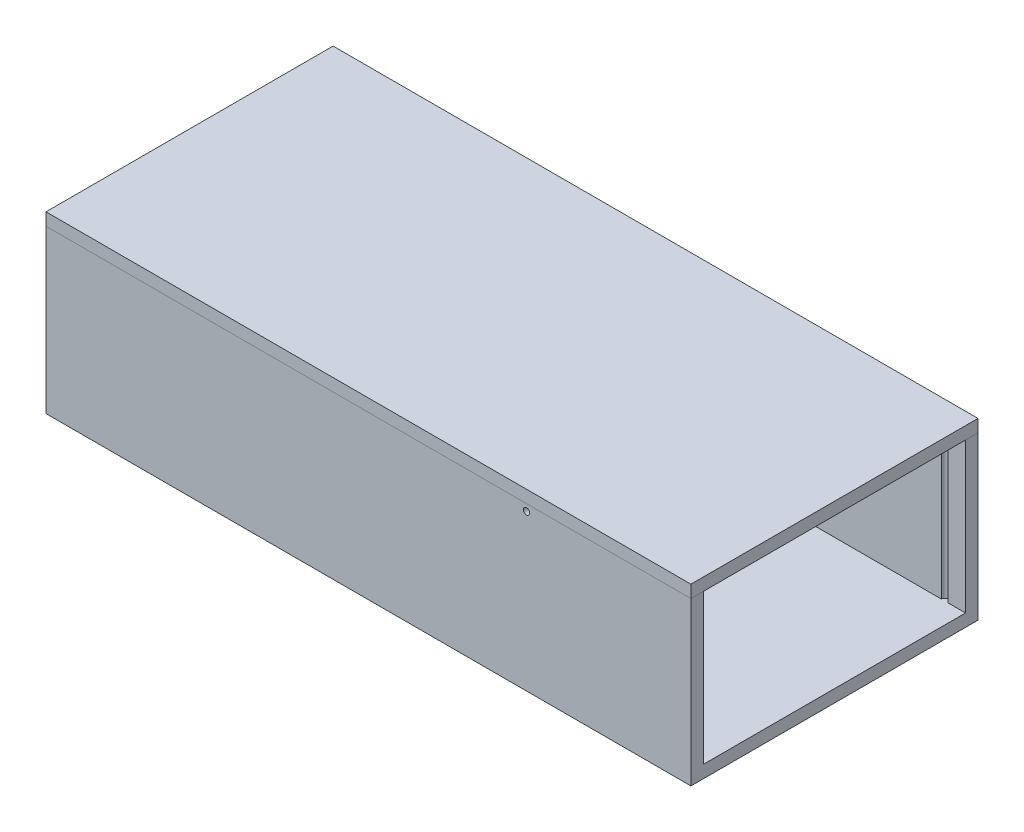
SolidWorks part; units mm, degrees
ref_plane "Plano frontal" through (0, 0, 0) normal (0, 0, 1) x (1, 0, 0)
ref_plane "Plano superior" through (0, 0, 0) normal (0, 1, 0) x (1, 0, 0)
ref_plane "Plano direito" through (0, 0, 0) normal (1, 0, 0) x (0, 0, -1)
sketch "Esboço1" plane through (0, 0, 0) normal (0, 1, 0) x (1, 0, 0)
  line L1 (0, 0) -> (155, 0)
  line L2 (0, 0) -> (0, 69)
  line L3 (0, 69) -> (155, 69)
  line L4 (155, 0) -> (155, 69)
  dimension "D1" = 69
  dimension "D2" = 155
extrude "Ressalto-extrusão1" add sketch "Esboço1" along normal blind 39
sketch "Esboço2" plane through (0, 39, 0) normal (0, 1, 0) x (1, 0, 0)
  line L0 (0, 0) -> (155, 0) construction
  line L1 (2, 3) -> (155, 3)
  line L2 (2, 3) -> (2, 66)
  line L3 (2, 66) -> (155, 66)
  line L4 (155, 3) -> (155, 66)
  line L5 (155, 69) -> (0, 69) construction
  line L6 (0, 69) -> (0, 0) construction
  dimension "D1" = 3
  dimension "D2" = 3
  dimension "D3" = 2
  dimension "D4" = 0
extrude "Corte-extrusão1" cut sketch "Esboço2" against normal offset from surface (36 mm away) 3 up to face at (77.5, 0, -34.5)
sketch "Esboço5" plane through (0, 39, 0) normal (0, 1, 0) x (1, 0, 0)
  line L0 (155, 66) -> (155, 69) construction
  line L1 (2, 3) -> (122.5, 3)
  line L2 (2, 3) -> (2, 5)
  line L3 (2, 5) -> (122.5, 5)
  line L4 (122.5, 3) -> (122.5, 5)
  line L5 (2, 66) -> (122.5, 66)
  line L6 (2, 66) -> (2, 64)
  line L7 (2, 64) -> (122.5, 64)
  line L8 (122.5, 66) -> (122.5, 64)
  point P13 (155, 67.5)
  dimension "D1" = 2
  dimension "D2" = 2
  dimension "D3" = 32.5
  dimension "D4" = 32.5
extrude "Ressalto-extrusão3" add sketch "Esboço5" against normal offset from surface (5.4 mm away) 26.5 from offset 4.1 up to face at (78.5, 3, -34.5) offset against normal yes
sketch "Esboço7" plane through (0, 39, 0) normal (0, 1, 0) x (1, 0, 0)
  line L0 (2, 3) -> (155, 3) construction
  line L1 (155, 66) -> (2, 66) construction
  line L2 (155, 66) -> (155, 69) construction
  circle A0 centre (150, 3) radius 0.8
  circle A1 centre (150, 66) radius 0.8
  dimension "D1" = 5
  dimension "D2" = 5
  dimension "D3" = 1.6
  dimension "D4" = 1.6
extrude "Corte-extrusão4" cut sketch "Esboço7" against normal up to surface (36 mm away) up to face at (78.5, 3, -34.5)
fillet "Filete5" [suppressed] radius 3
sketch "Esboço8" plane through (0, 39, 0) normal (0, 1, 0) x (1, 0, 0)
  line L0 (0, 0) -> (155, 0) construction
  line L1 (155, 0) -> (155, 3) construction
  line L2 (0, 69) -> (0, 0) construction
  line L3 (155, 69) -> (0, 69) construction
  line L4 (155, 66) -> (155, 69) construction
  circle A0 centre (3, 3) radius 0.9
  circle A1 centre (120, 3) radius 0.9
  circle A2 centre (120, 66) radius 0.9
  circle A3 centre (3, 66) radius 0.9
  dimension "D1" = 1.8
  dimension "D2" = 1.8
  dimension "D3" = 1.8
  dimension "D4" = 1.8
  dimension "D5" = 3
  dimension "D6" = 35
  dimension "D7" = 3
  dimension "D8" = 3
  dimension "D9" = 3
  dimension "D10" = 3
  dimension "D11" = 35
  dimension "D12" = 3
extrude "Corte-extrusão3" [suppressed] cut sketch "Esboço8" against normal up to surface (8.5 mm away)
sketch "Esboço10" plane through (0, 39, 0) normal (0, 1, 0) x (1, 0, 0)
  line L0 (2, 3) -> (149.2, 3) construction
  line L1 (149.2, 66) -> (2, 66) construction
  line L2 (2, 66) -> (2, 3) construction
  line L3 (2, 66) -> (2, 3) construction
  circle A0 centre (7, 3) radius 0.75
  circle A1 centre (7, 66) radius 0.75
  dimension "D1" = 1.5
  dimension "D2" = 1.5
  dimension "D3" = 5
  dimension "D4" = 5
extrude "Ressalto-extrusão5" add sketch "Esboço10" against normal up to surface (4.1 mm away) up to face at (62.25, 34.9, -4)
sketch "Esboço9" plane through (0, 39, 0) normal (0, 1, 0) x (1, 0, 0)
  line L0 (2, 66) -> (2, 3) construction
  line L1 (155, 0) -> (0, 0)
  line L2 (155, 0) -> (155, 69)
  line L3 (155, 69) -> (0, 69)
  line L4 (0, 0) -> (0, 69)
  line L5 (149.2, 66) -> (7.75, 66) construction
  dimension "D1" = 69
  dimension "D2" = 155
  dimension "D3" = 2
  dimension "D4" = 3
extrude "Ressalto-extrusão4" add sketch "Esboço9" along normal blind 3
sketch "Esboço11" plane through (0, 0, 0) normal (-1, 0, 0) x (0, 0, 1)
  line L1 (-62.35, 37) -> (-44.25, 37)
  line L2 (-62.35, 37) -> (-62.35, 21.9)
  line L3 (-62.35, 21.9) -> (-44.25, 21.9)
  line L4 (-44.25, 37) -> (-44.25, 21.9)
extrude "Ressalto-extrusão6" add sketch "Esboço11" along normal blind 5
sketch "Esboço12" plane through (-5, 0, 0) normal (-1, 0, 0) x (0, 0, 1)
  line L1 (-60.8, 35.25) -> (-45.8, 35.25)
  line L2 (-60.8, 35.25) -> (-60.8, 23.75)
  line L3 (-60.8, 23.75) -> (-45.8, 23.75)
  line L4 (-45.8, 35.25) -> (-45.8, 23.75)
extrude "Corte-extrusão5" cut sketch "Esboço12" against normal blind 9
sketch "Esboço14" plane through (-5, 0, 0) normal (-1, 0, 0) x (0, 0, 1)
  line L0 (-62.35, 21.9) -> (-44.25, 21.9) construction
  line L1 (-60.05, 21.9) -> (-46.55, 21.9)
  line L2 (-60.05, 21.9) -> (-60.05, 23.75)
  line L3 (-60.05, 23.75) -> (-46.55, 23.75)
  line L4 (-46.55, 21.9) -> (-46.55, 23.75)
  line L5 (-60.8, 23.75) -> (-45.8, 23.75) construction
  line L6 (-62.35, 37) -> (-62.35, 21.9) construction
  dimension "D1" = 13.5
  dimension "D2" = 2.3
extrude "Corte-extrusão6" cut sketch "Esboço14" against normal through all
sketch "Esboço15" plane through (0, 0, -69) normal (0, 0, -1) x (-1, 0, 0)
  line L0 (-122.5, 34.9) -> (-7.75, 34.9) construction
  line L1 (-122.5, 29.5) -> (-122.5, 34.9) construction
  circle A0 centre (-115.5, 37.4) radius 0.75
  dimension "D1" = 2.5
  dimension "D2" = 1.5
  dimension "D3" = 7
extrude "Corte-extrusão7" cut sketch "Esboço15" against normal through all
